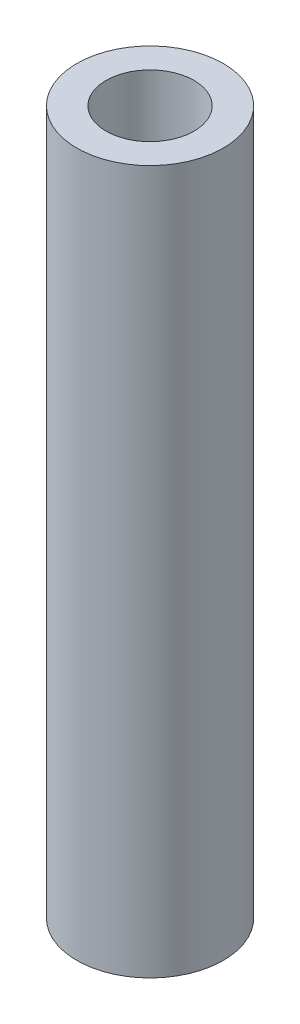
SolidWorks part; units mm, degrees
material "Thornel Mat VMA"
ref_plane "Front Plane" through (0, 0, 0) normal (0, 0, 1) x (1, 0, 0)
ref_plane "Top Plane" through (0, 0, 0) normal (0, 1, 0) x (1, 0, 0)
ref_plane "Right Plane" through (0, 0, 0) normal (1, 0, 0) x (0, 0, -1)
sketch "Sketch1" plane through (0, 0, 0) normal (0, 1, 0) x (1, 0, 0)
  circle A0 centre (0, 0) radius 7.9375
  circle A1 centre (0, 0) radius 4.7625
  dimension "D1" = 15.875
  dimension "D2" = 9.525
extrude "Boss-Extrude1" add sketch "Sketch1" along normal blind 76.2
